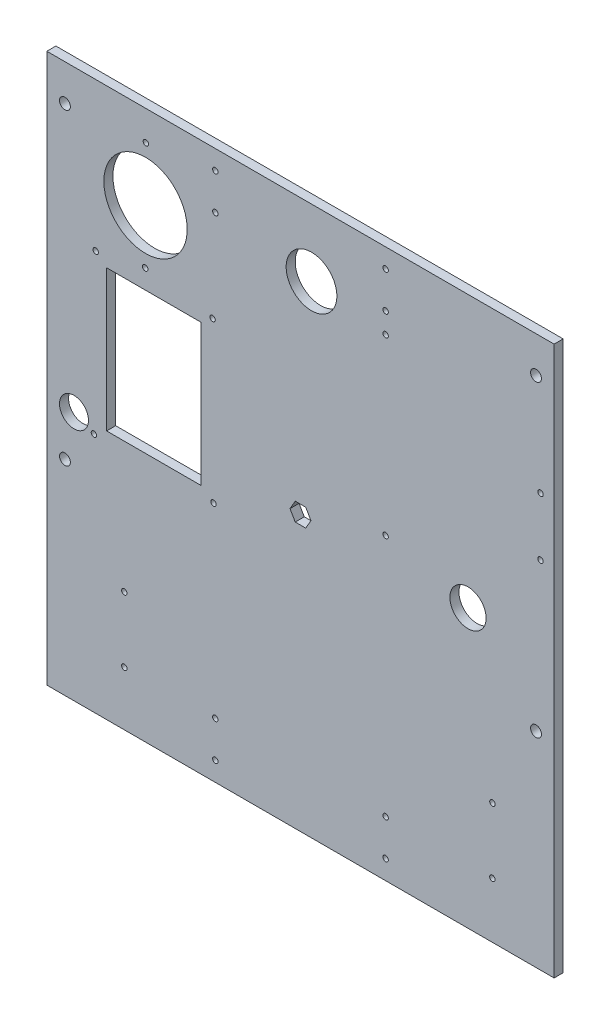
SolidWorks part; units mm, degrees
ref_plane "Plan de face" through (0, 0, 0) normal (0, 0, 1) x (1, 0, 0)
ref_plane "Plan de dessus" through (0, 0, 0) normal (0, 1, 0) x (1, 0, 0)
ref_plane "Plan de droite" through (0, 0, 0) normal (1, 0, 0) x (0, 0, -1)
sketch "Esquisse1" plane through (0, 0, 0) normal (0, 0, 1) x (1, 0, 0)
  line L1 (0, 0) -> (280, 0)
  line L2 (0, 0) -> (0, 210)
  line L3 (0, 210) -> (280, 210)
  line L4 (280, 0) -> (280, 210)
  dimension "D1" = 210
  dimension "D2" = 280
extrude "Boss.-Extru.1" add sketch "Esquisse1" along normal blind 5
sketch "Esquisse2" plane through (0, 0, 0) normal (0, 0, 1) x (1, 0, 0)
  line L0 (280, 210) -> (0, 210) construction
  line L1 (85, 123) -> (33, 123)
  line L2 (0, 0) -> (280, 0) construction
  line L3 (0, 0) -> (0, 210) construction
  line L4 (0, 210) -> (280, 210) construction
  line L5 (280, 0) -> (280, 210) construction
  line L6 (85, 123) -> (85, 45)
  line L7 (137.1132, 63.5) -> (134.2265, 58.5)
  line L8 (134.2265, 58.5) -> (137.1132, 53.5)
  line L9 (137.1132, 53.5) -> (142.8868, 53.5)
  line L10 (142.8868, 53.5) -> (145.7735, 58.5)
  line L11 (145.7735, 58.5) -> (142.8868, 63.5)
  line L12 (142.8868, 63.5) -> (137.1132, 63.5)
  line L13 (85, 45) -> (33, 45)
  line L14 (33, 123) -> (33, 45)
  circle A0 centre (270, 190) radius 3
  circle A1 centre (10, 190) radius 3
  circle A2 centre (10, 20) radius 3
  circle A3 centre (270, 20) radius 3
  circle A4 centre (140, 58.5) radius 5 construction
  circle A5 centre (187, 168) radius 1.5
  circle A6 centre (187, 72) radius 1.5
  circle A7 centre (91.5, 128) radius 1.5
  circle A8 centre (27, 128) radius 1.5
  circle A9 centre (92, 40) radius 1.5
  circle A10 centre (26, 40) radius 1.5
  circle A11 centre (15, 45) radius 8
  circle A12 centre (146.0937, 173) radius 14
  circle A13 centre (232.4771, 60.1974) radius 10
  circle A14 centre (272.5, 103) radius 1.5
  circle A15 centre (272.5, 135) radius 1.5
  point P50 (139.6216, 103.8992)
  point P51 (136.4212, 61.4587)
  point P52 (133.6477, 78.8616)
  dimension "D1" = 6
  dimension "D2" = 6
  dimension "D3" = 6
  dimension "D4" = 6
  dimension "D5" = 20
  dimension "D6" = 10
  dimension "D7" = 20
  dimension "D8" = 10
  dimension "D9" = 10
  dimension "D10" = 20
  dimension "D11" = 10
  dimension "D12" = 20
  dimension "D13" = 10
  dimension "D14" = 3
  dimension "D15" = 3
  dimension "D16" = 96
  dimension "D17" = 93
  dimension "D19" = 5
  dimension "D26" = 7
  dimension "D27" = 5
  dimension "D29" = 6.5
  dimension "D30" = 5
  dimension "D32" = 3
  dimension "D33" = 3
  dimension "D34" = 3
  dimension "D35" = 3
  dimension "D37" = 42
  dimension "D38" = 16
  dimension "D39" = 28
  dimension "D40" = 20
  dimension "D18" = 93
  dimension "D41" = 3
  dimension "D42" = 3
  dimension "D43" = 7.5
  dimension "D44" = 7.5
  dimension "D45" = 32
  dimension "D46" = 75
  dimension "D20" = 52
  dimension "D21" = 78
  dimension "D22" = 45
  dimension "D23" = 85
  dimension "D24" = 5
  dimension "D25" = 7
  dimension "D28" = 5
  dimension "D31" = 6
  dimension "D36" = 18
  dimension "D47" = 151.5
  dimension "D48" = 140
extrude "Enlèv. mat.-Extru.1" cut sketch "Esquisse2" along normal through all
sketch "Esquisse5" plane through (0, 0, 0) normal (0, 0, -1) x (-1, 0, 0)
  circle A0 centre (-93, 179.4) radius 1.5
  circle A1 centre (-93, 199.4) radius 1.5
  circle A2 centre (-187, 199.4) radius 1.5
  circle A3 centre (-187, 179.4) radius 1.5
  dimension "D1" = 3
  dimension "D2" = 3
  dimension "D3" = 3
  dimension "D4" = 3
extrude "Enlèv. mat.-Extru.3" cut sketch "Esquisse5" against normal through all
sketch "Esquisse6" plane through (0, 0, 0) normal (0, 0, -1) x (-1, 0, 0)
  line L1 (-280, 0) -> (0, 0)
  line L2 (-280, 0) -> (-280, -93)
  line L3 (-280, -93) -> (0, -93)
  line L4 (0, 0) -> (0, -93)
  point P5 (-280, -46.5)
  dimension "D1" = 93
  dimension "D2" = 280
extrude "Boss.-Extru.4" add sketch "Esquisse6" against normal blind 5
sketch "Esquisse7" plane through (0, 0, 0) normal (0, 0, -1) x (-1, 0, 0)
  circle A0 centre (-42.7853, -27.0556) radius 1.5
  circle A3 centre (-42.7733, -63.0396) radius 1.5
  dimension "D3" = 3
  dimension "D4" = 3
extrude "Enlèv. mat.-Extru.4" cut sketch "Esquisse7" against normal through all
sketch "Esquisse8" plane through (0, 0, 0) normal (0, 0, -1) x (-1, 0, 0)
  circle A0 centre (-245.9449, -62.3449) radius 1.5
  circle A1 centre (-245.9449, -26.3609) radius 1.5
  dimension "D2" = 3
  dimension "D3" = 3
extrude "Enlèv. mat.-Extru.5" cut sketch "Esquisse8" against normal through all
sketch "Esquisse9" plane through (0, 0, 0) normal (0, 0, -1) x (-1, 0, 0)
  circle A0 centre (-93, -62.4) radius 1.5
  circle A1 centre (-93, -82.4) radius 1.5
  circle A2 centre (-93, -82.4) radius 1.5 construction
  circle A3 centre (-187, -82.4) radius 1.5
  circle A4 centre (-187, -62.4) radius 1.5
  dimension "D1" = 3
  dimension "D2" = 3
  dimension "D3" = 0
  dimension "D4" = 3
  dimension "D5" = 3
extrude "Enlèv. mat.-Extru.6" cut sketch "Esquisse9" against normal through all
sketch "Esquisse14" plane through (0, 0, 0) normal (0, 0, -1) x (-1, 0, 0)
  circle A0 centre (-54.4827, 163.5701) radius 23
  circle A1 centre (-54.6491, 193.5697) radius 1.5
  circle A2 centre (-54.3162, 133.5706) radius 1.5
  dimension "D1" = 3
  dimension "D2" = 46
  dimension "D3" = 3
extrude "Enlèv. mat.-Extru.11" cut sketch "Esquisse14" against normal through all
